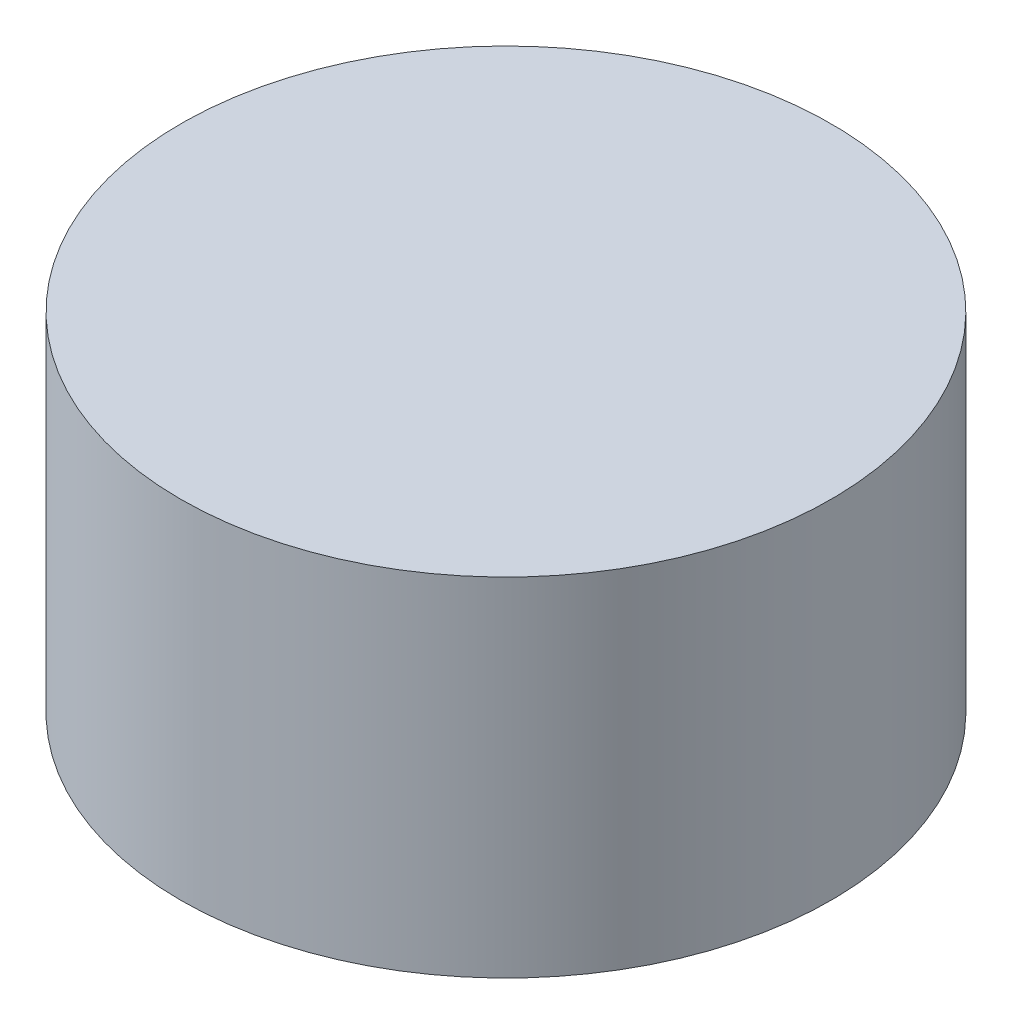
SolidWorks part; units mm, degrees
ref_plane "Front Plane" through (0, 0, 0) normal (0, 0, 1) x (1, 0, 0)
ref_plane "Top Plane" through (0, 0, 0) normal (0, 1, 0) x (1, 0, 0)
ref_plane "Right Plane" through (0, 0, 0) normal (1, 0, 0) x (0, 0, -1)
sketch "Sketch1" plane through (0, 0, 0) normal (0, 1, 0) x (1, 0, 0)
  circle A0 centre (0, 0) radius 11.0363
  dimension "D1" = 22.0726
extrude "Boss-Extrude1" add sketch "Sketch1" along normal mid plane 11.7856
